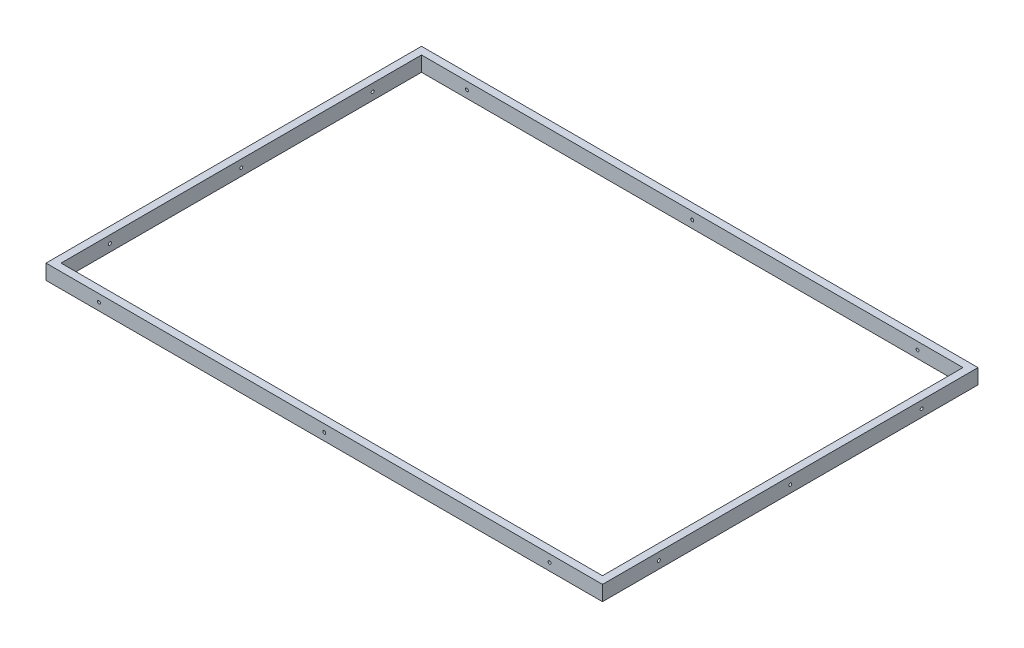
SolidWorks part; units mm, degrees
ref_plane "前视基准面" through (0, 0, 0) normal (0, 0, 1) x (1, 0, 0)
ref_plane "上视基准面" through (0, 0, 0) normal (0, 1, 0) x (1, 0, 0)
ref_plane "右视基准面" through (0, 0, 0) normal (1, 0, 0) x (0, 0, -1)
other "Configuration Table"
sketch "草图1" plane through (0, 0, 0) normal (0, 1, 0) x (1, 0, 0)
  line L1 (-74.1, -50) -> (74.1, -50)
  line L2 (-74.1, -50) -> (-74.1, 50)
  line L3 (-74.1, 50) -> (74.1, 50)
  line L4 (74.1, -50) -> (74.1, 50)
  line L5 (-74.1, -50) -> (74.1, 50) construction
  line L6 (-74.1, 50) -> (74.1, -50) construction
  line L7 (-72.1, 48) -> (72.1, 48)
  line L8 (-72.1, 48) -> (-72.1, -48)
  line L9 (-72.1, -48) -> (72.1, -48)
  line L10 (72.1, 48) -> (72.1, -48)
  dimension "D3" = 2
  dimension "D4" = 2
  dimension "D1" = 100
  dimension "D2" = 148.2
  dimension "D5" = 2
  dimension "D6" = 2
extrude "凸台-拉伸1" add sketch "草图1" along normal blind 4
sketch "草图2" plane through (0, 0, 50) normal (0, 0, 1) x (1, 0, 0)
  line L0 (-60, 2) -> (0, 2) construction
  line L1 (0, 2) -> (60, 2) construction
  line L2 (0, 4) -> (0, 2) construction
  line L3 (-74.1, 4) -> (74.1, 4) construction
  line L4 (0, 2) -> (0, 0) construction
  circle A0 centre (0, 2) radius 0.4
  circle A1 centre (-60, 2) radius 0.4
  circle A2 centre (60, 2) radius 0.4
  dimension "D2" = 0.8
  dimension "D1" = 60
extrude "切除-拉伸1" cut sketch "草图2" against normal through all
sketch "草图3" plane through (-74.1, 0, 0) normal (-1, 0, 0) x (0, 0, 1)
  line L0 (0, 0) -> (0, 4) construction
  line L1 (-50, 0) -> (50, 0) construction
  line L2 (-50, 4) -> (50, 4) construction
  line L3 (-35, 2) -> (0, 2) construction
  line L4 (0, 2) -> (35, 2) construction
  circle A0 centre (0, 2) radius 0.4
  circle A1 centre (35, 2) radius 0.4
  circle A2 centre (-35, 2) radius 0.4
  dimension "D1" = 0.8
  dimension "D2" = 35
extrude "切除-拉伸2" cut sketch "草图3" against normal through all
